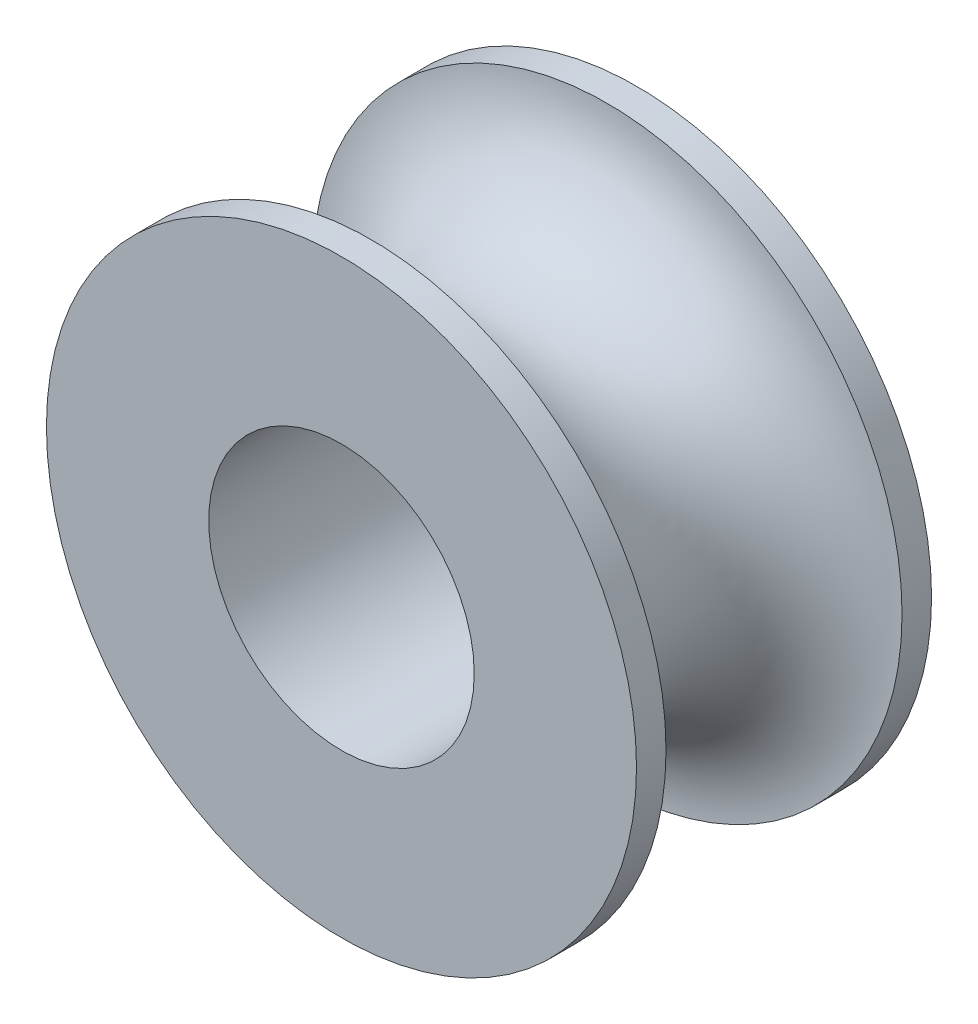
SolidWorks part; units mm, degrees
material "黄铜"
ref_plane "前视基准面" through (0, 0, 0) normal (0, 0, 1) x (1, 0, 0)
ref_plane "上视基准面" through (0, 0, 0) normal (0, 1, 0) x (1, 0, 0)
ref_plane "右视基准面" through (0, 0, 0) normal (1, 0, 0) x (0, 0, -1)
sketch "草图1" plane through (0, 0, 0) normal (0, 1, 0) x (1, 0, 0)
  line L1 (0, -2.5) -> (5, -2.5)
  line L3 (0, 2.5) -> (5, 2.5)
  line L4 (5, -2.5) -> (5, -2)
  line L5 (0, 2.5) -> (0, -2.5)
  line L8 (5, 2) -> (5, 2.5)
  arc A1 (5, -2) -> (5, 2) centre (5, 0) cw
  point P0 (0, 0)
  dimension "D3" = 5
  dimension "D1" = 2
  dimension "D2" = 5
ref_axis "基准轴1" through (0, 0, -2.75) along (0, 0, 1)
revolve "旋转5" add sketch "草图1" angle 360 about axis through (0, 0, -2.75) along (0, 0, 1)
sketch "草图2" plane through (0, 0, 0) normal (0, 0, 1) x (1, 0, 0)
  circle A0 centre (0, 0) radius 2.25
  dimension "D1" = 4.5
extrude "切除-拉伸1" cut sketch "草图2" against normal through all both and the other way through all
